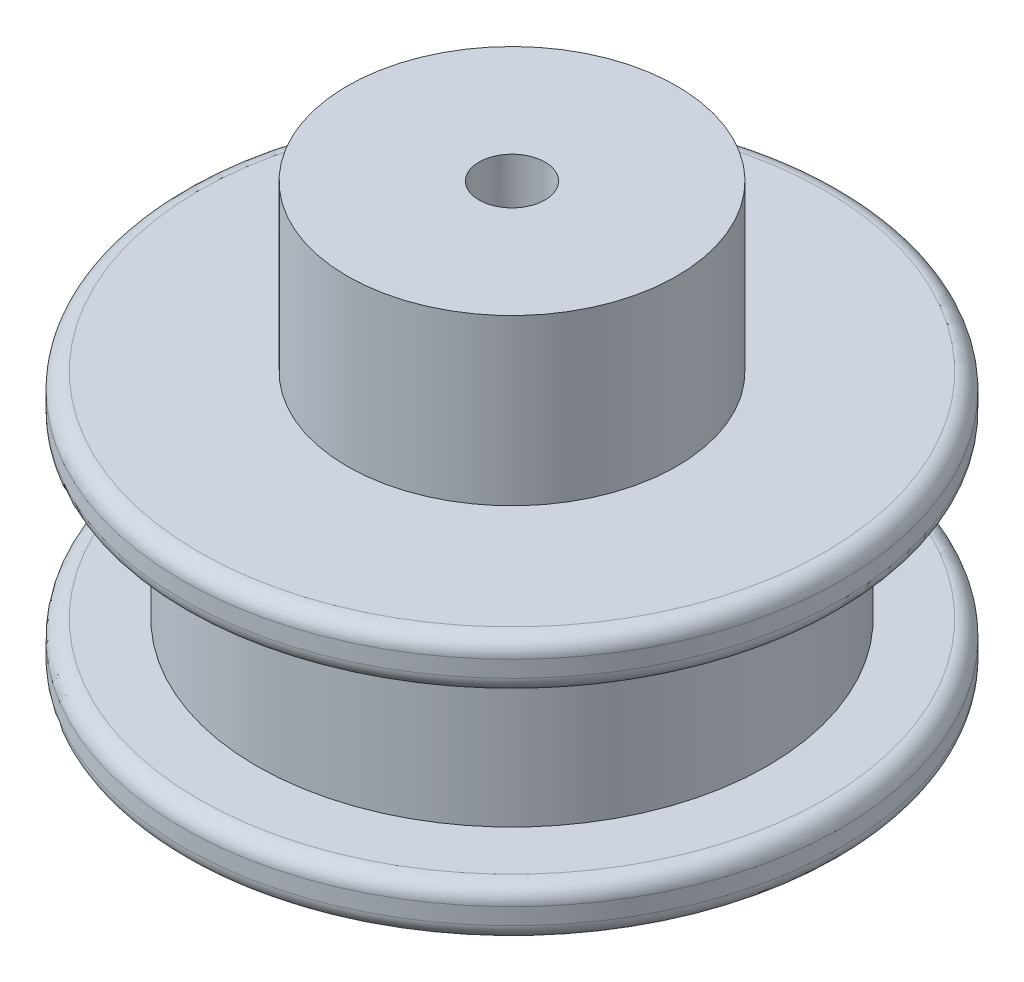
SolidWorks part; units mm, degrees
material "6061 合金"
ref_plane "前视基准面" through (0, 0, 0) normal (0, 0, 1) x (1, 0, 0)
ref_plane "上视基准面" through (0, 0, 0) normal (0, 1, 0) x (1, 0, 0)
ref_plane "右视基准面" through (0, 0, 0) normal (1, 0, 0) x (0, 0, -1)
other "Configuration Table"
sketch "草图1" plane through (0, 0, 0) normal (0, 1, 0) x (1, 0, 0)
  circle A0 centre (0, 0) radius 15.5
  dimension "D1" = 31
extrude "凸台-拉伸1" add sketch "草图1" along normal blind 10
sketch "草图2" plane through (0, 10, 0) normal (0, 1, 0) x (1, 0, 0)
  circle A0 centre (0, 0) radius 20
  dimension "D1" = 40
extrude "凸台-拉伸2" add sketch "草图2" along normal blind 3
sketch "草图3" plane through (0, 0, 0) normal (0, -1, 0) x (1, 0, 0)
  circle A0 centre (0, 0) radius 20
  dimension "D1" = 40
extrude "凸台-拉伸3" add sketch "草图3" along normal blind 3
fillet "圆角2" radius 1 4 edges at (0, 0, -20) (0, -3, -20) (0, 10, 20) (0, 13, 20)
sketch "草图4" plane through (0, 13, 0) normal (0, 1, 0) x (1, 0, 0)
  circle A0 centre (0, 0) radius 2
  dimension "D1" = 4
extrude "切除-拉伸1" cut sketch "草图4" against normal through all
sketch "草图5" plane through (0, 13, 0) normal (0, 1, 0) x (1, 0, 0)
  circle A0 centre (0, 0) radius 10
  circle A1 centre (0, 0) radius 2 construction
  circle A2 centre (0, 0) radius 2
  dimension "D1" = 20
extrude "凸台-拉伸4" add sketch "草图5" along normal blind 10
sketch "草图6" plane through (0, 0, 0) normal (0, 0, 1) x (1, 0, 0)
  circle A0 centre (0, 18.1452) radius 2
extrude "切除-拉伸2" cut sketch "草图6" against normal through all
cosmetic thread "装饰螺纹线1" parameters "D2"=5
